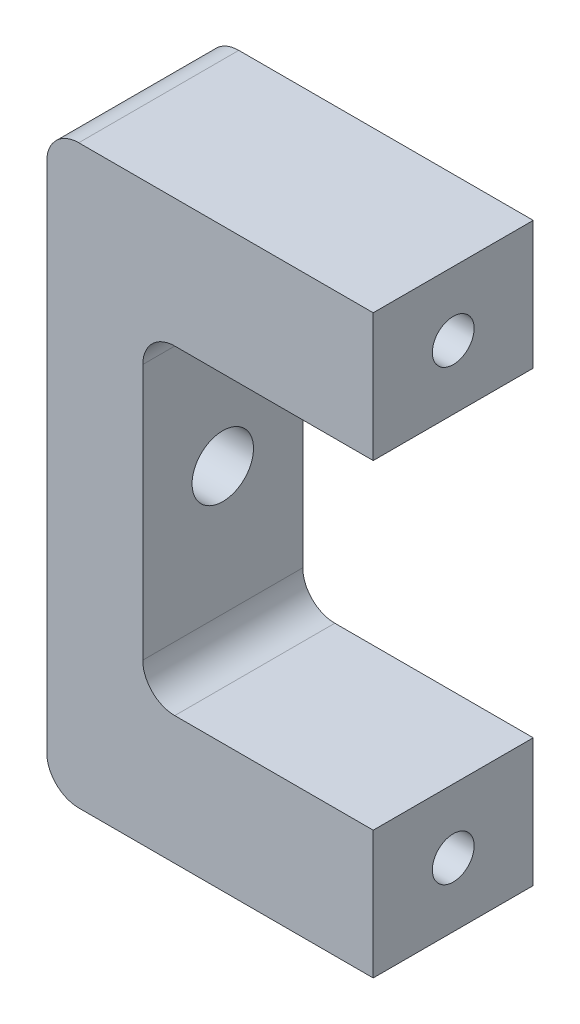
SolidWorks part; units mm, degrees
ref_plane "Front" through (0, 0, 0) normal (0, 0, 1) x (1, 0, 0)
ref_plane "Top" through (0, 0, 0) normal (0, 1, 0) x (1, 0, 0)
ref_plane "Right" through (0, 0, 0) normal (1, 0, 0) x (0, 0, -1)
sketch "Sketch2" plane through (0, 0, 0) normal (0, 0, 1) x (1, 0, 0)
  line L0 (18, 25) -> (18, 45)
  line L1 (18, 25) -> (-18, 25)
  line L2 (18, 25) -> (18, -25)
  line L3 (18, -25) -> (-18, -25)
  line L4 (-18, 25) -> (-18, -25)
  line L5 (18, 25) -> (-18, -25) construction
  line L6 (18, -25) -> (-18, 25) construction
  line L7 (33, 45) -> (-33, 45)
  line L8 (33, 45) -> (33, -45)
  line L9 (33, -45) -> (-33, -45)
  line L10 (-33, 45) -> (-33, -45)
  line L11 (33, 45) -> (-33, -45) construction
  line L12 (33, -45) -> (-33, 45) construction
  line L13 (18, -25) -> (18, -45)
  point P0 (0, 0)
  point P6 (0, 0)
  dimension "D1" = 36
  dimension "D2" = 50
  dimension "D3" = 15
  dimension "D4" = 20
extrude "Boss-Extrude1" add sketch "Sketch2" along normal blind 25 contours L13 L3 L4 L1 L0 L7 L10 L9
sketch "Sketch3" plane through (-18, 0, 0) normal (1, 0, 0) x (0, 0, -1)
  line L0 (-25, 25) -> (0, 25) construction
  circle A0 centre (-12.5, 0) radius 4.8
  point P5 (-12.5, 25)
  dimension "D1" = 9.6
extrude "Cut-Extrude1" cut sketch "Sketch3" against normal blind 7.5
fillet "Fillet1" radius 5 4 edges at (-18, -25, 12.5) (-18, 25, 12.5) (-33, -45, 12.5) (-33, 45, 12.5)
hole_wizard "CBORE for 1/4 Socket Head Cap Screw1" positions "Sketch4" profile "Sketch5" counterbore size "1/4" standard "ANSI Inch" end condition up to next
sketch "Sketch4" plane through (-33, 0, 0) normal (-1, 0, 0) x (0, 0, 1)
  line L0 (25, 45) -> (0, 45) construction
  line L1 (25, -45) -> (0, -45) construction
  point P0 (12.5, 35)
  point P2 (12.5, -35)
  point P10 (12.5, 45)
  dimension "D1" = 10
  dimension "D2" = 10
sketch "Sketch5" plane through (-33, 35, 12.5) normal (0, 1, 0) x (0, 0, 1)
  line L0 (0, 0) -> (0, 51)
  line L1 (0, 51) -> (3.2639, 51)
  line L3 (3.2639, 51) -> (3.2639, 22.225)
  line L4 (3.2639, 22.225) -> (5.5562, 22.225)
  line L5 (5.5562, 22.225) -> (5.5563, 0)
  line L7 (5.5563, 0) -> (0, 0)
  line L11 (0, -6.35) -> (0, 107.95) construction
  dimension "Thru Hole Dia." = 6.5278
  dimension "Thru Hole Depth" = 51
  dimension "C'Bore Dia." = 11.1125
  dimension "C'Bore Depth" = 22.225
